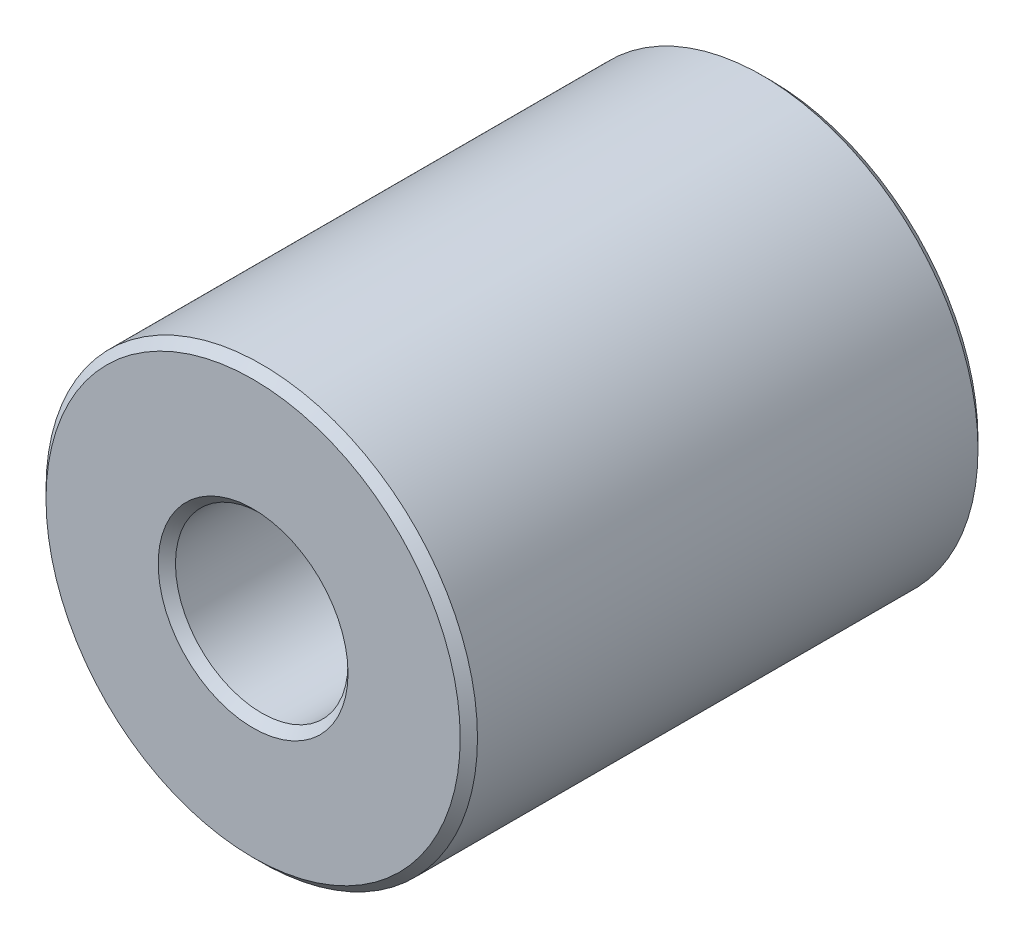
SolidWorks part; units mm, degrees
ref_plane "Ön Düzlem" through (0, 0, 0) normal (0, 0, 1) x (1, 0, 0)
ref_plane "Üst Düzlem" through (0, 0, 0) normal (0, 1, 0) x (1, 0, 0)
ref_plane "Sağ Düzlem" through (0, 0, 0) normal (1, 0, 0) x (0, 0, -1)
sketch "Çizim1" plane through (0, 0, 0) normal (0, 0, 1) x (1, 0, 0)
  circle A0 centre (0, 0) radius 12.5
  dimension "D1" = 25
extrude "Yükseklik-Ekstrüzyon1" add sketch "Çizim1" along normal blind 30
sketch "Çizim2" plane through (0, 0, 30) normal (0, 0, 1) x (1, 0, 0)
  circle A0 centre (0, 0) radius 5
  dimension "D1" = 10
extrude "Kes-Ekstrüzyon1" cut sketch "Çizim2" against normal blind 25
chamfer "Pah1" distance 0.5 angle 45 3 edges at (12.5, 0, 30) (5, 0, 30) (12.5, 0, 0)
